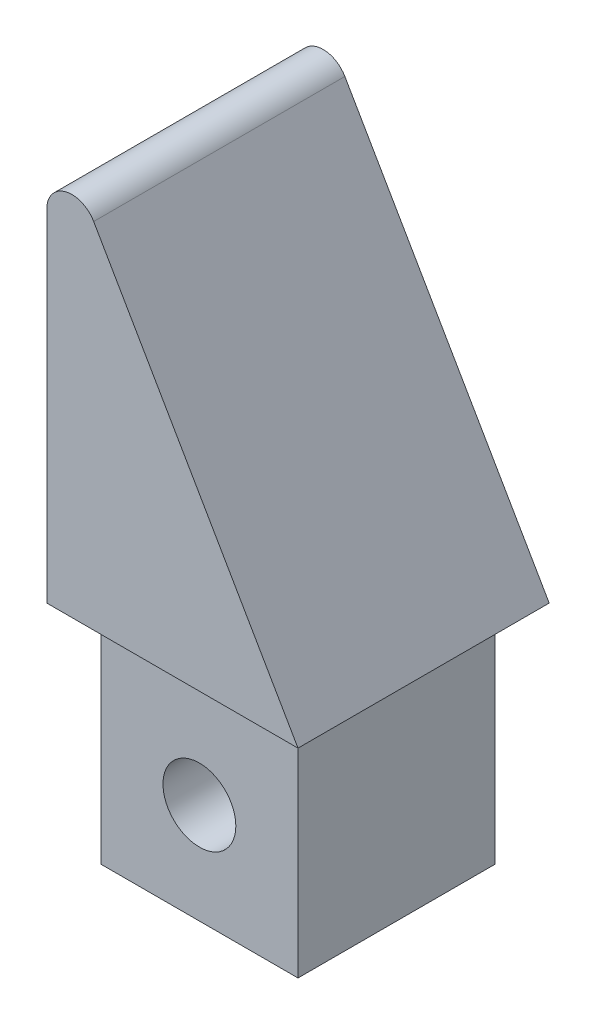
SolidWorks part; units mm, degrees
ref_plane "正面" through (0, 0, 0) normal (0, 0, 1) x (1, 0, 0)
ref_plane "平面" through (0, 0, 0) normal (0, 1, 0) x (1, 0, 0)
ref_plane "右側面" through (0, 0, 0) normal (1, 0, 0) x (0, 0, -1)
sketch "ｽｹｯﾁ1" plane through (0, 0, 0) normal (0, 1, 0) x (1, 0, 0)
  line L1 (-3.925, -3.925) -> (3.925, -3.925)
  line L2 (-3.925, -3.925) -> (-3.925, 3.925)
  line L3 (-3.925, 3.925) -> (3.925, 3.925)
  line L4 (3.925, -3.925) -> (3.925, 3.925)
  line L5 (-3.925, -3.925) -> (3.925, 3.925) construction
  line L6 (-3.925, 3.925) -> (3.925, -3.925) construction
  point P0 (0, 0)
  dimension "D1" = 7.85
extrude "ﾎﾞｽ - 押し出し1" add sketch "ｽｹｯﾁ1" along normal blind 10
sketch "ｽｹｯﾁ2" plane through (0, 10, 0) normal (0, 1, 0) x (1, 0, 0)
  line L1 (-5, -5) -> (5, -5)
  line L2 (-5, -5) -> (-5, 5)
  line L3 (-5, 5) -> (5, 5)
  line L4 (5, -5) -> (5, 5)
  line L5 (-5, -5) -> (5, 5) construction
  line L6 (-5, 5) -> (5, -5) construction
  point P0 (0, 0)
  dimension "D1" = 10
extrude "ﾎﾞｽ - 押し出し2" add sketch "ｽｹｯﾁ2" along normal blind 30
sketch "ｽｹｯﾁ3" plane through (0, 0, 5) normal (0, 0, 1) x (1, 0, 0)
  line L0 (5, 10) -> (-5, 27.3205)
  line L4 (-5, 10) -> (5, 10)
  line L5 (5, 10) -> (5, 40)
  line L6 (5, 40) -> (-5, 40)
  line L7 (-5, 40) -> (-5, 10)
  line L8 (-5, 10) -> (5, 10)
  line L9 (5, 10) -> (5, 40)
  line L10 (5, 40) -> (-5, 40)
  line L11 (-5, 40) -> (-5, 10)
  line M7 (5, 10) -> (5, 40)
  line M8 (5, 40) -> (-5, 40)
  line M9 (-5, 40) -> (-5, 10)
  dimension "D2" = 60
  dimension "D1" = 0
extrude "ｶｯﾄ - 押し出し1" cut sketch "ｽｹｯﾁ3" against normal blind 30 contours L0 M7 M8 M9
fillet "ﾌｨﾚｯﾄ1" radius 1 1 edges at (-5, 27.3205, 0)
chamfer "面取り1" distance 1 angle 45 4 edges at (0, 0, -3.925) (-3.925, 0, 0) (0, 0, 3.925) (3.925, 0, 0)
sketch "ｽｹｯﾁ4" plane through (0, 0, 3.925) normal (0, 0, 1) x (1, 0, 0)
  line L0 (0, 10) -> (0, 5) construction
  line L1 (-5, 10) -> (5, 10) construction
  circle A0 centre (0, 5) radius 1.45
  dimension "D2" = 2.9
  dimension "D1" = 5
extrude "ｶｯﾄ - 押し出し2" cut sketch "ｽｹｯﾁ4" against normal blind 30
